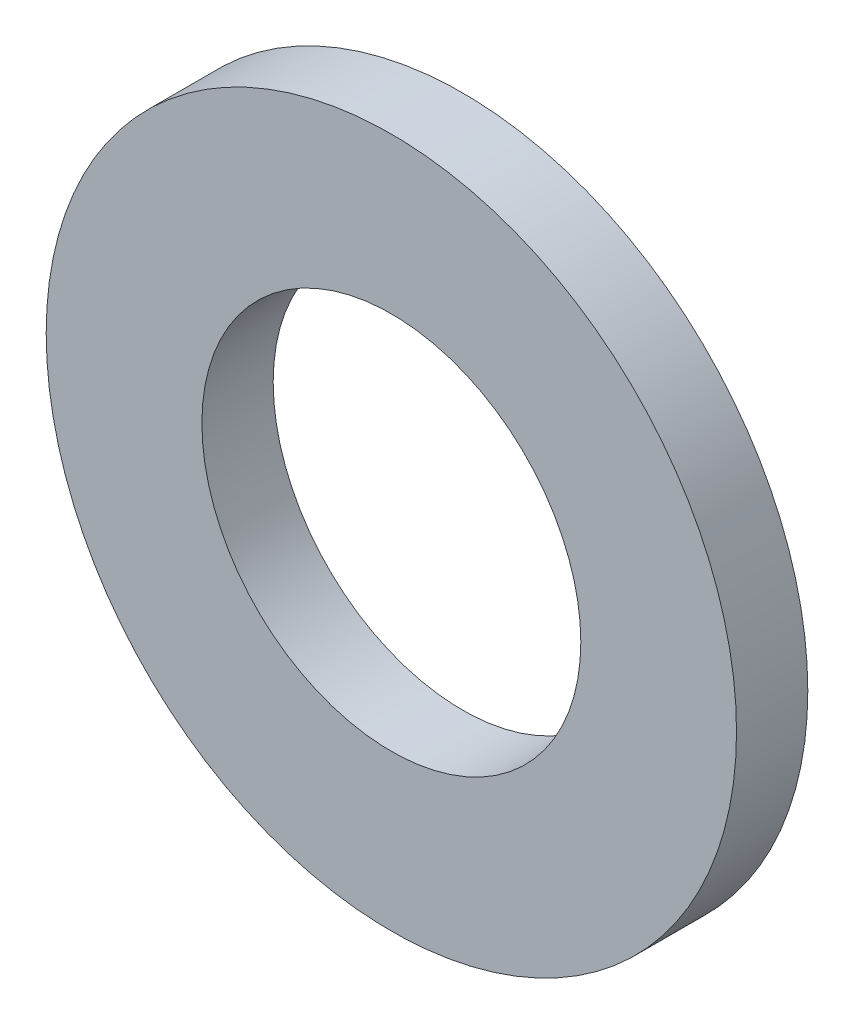
SolidWorks part; units mm, degrees
ref_plane "Piano frontale" through (0, 0, 0) normal (0, 0, 1) x (1, 0, 0)
ref_plane "Piano superiore" through (0, 0, 0) normal (0, 1, 0) x (1, 0, 0)
ref_plane "Piano destro" through (0, 0, 0) normal (1, 0, 0) x (0, 0, -1)
sketch "Schizzo2" plane through (0, 0, 0) normal (0, 0, 1) x (1, 0, 0)
  circle A0 centre (0, 0) radius 2.76
  circle A1 centre (0, 0) radius 1.515
  dimension "D1" = 3.03
  dimension "D2" = 5.52
extrude "Estrusione-Estrusione1" add sketch "Schizzo2" along normal blind 0.57
